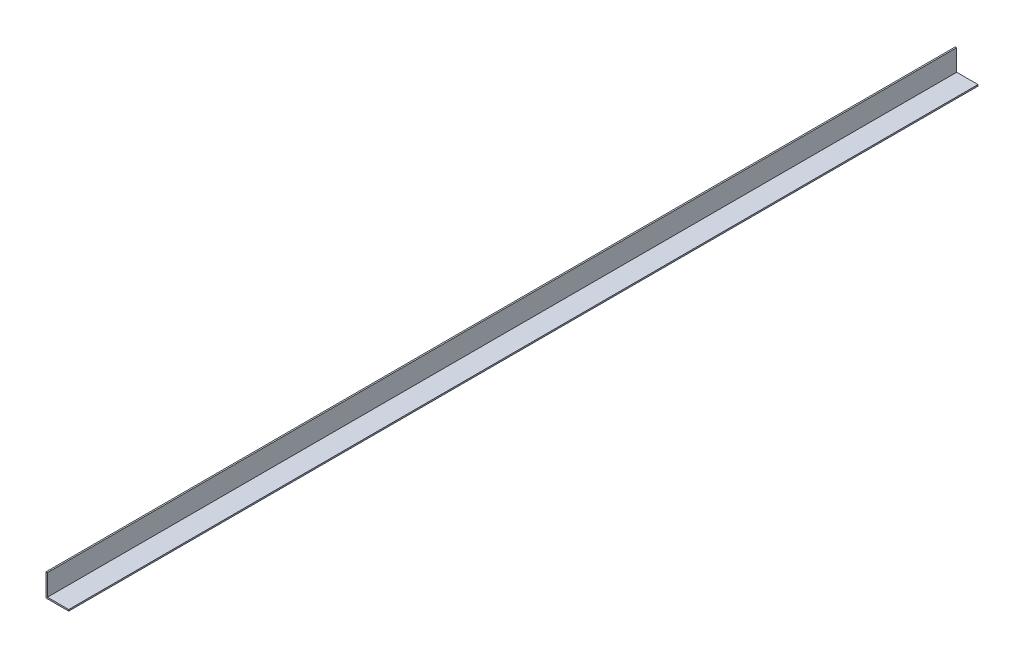
SolidWorks part; units mm, degrees
material "ASTM A36 Acero"
ref_plane "Alzado" through (0, 0, 0) normal (0, 0, 1) x (1, 0, 0)
ref_plane "Planta" through (0, 0, 0) normal (0, 1, 0) x (1, 0, 0)
ref_plane "Vista lateral" through (0, 0, 0) normal (1, 0, 0) x (0, 0, -1)
sketch "Croquis1" plane through (0, 0, 0) normal (0, 0, 1) x (1, 0, 0)
  line L0 (0, 152.4) -> (0, 0)
  line L1 (0, 0) -> (152.4, 0)
  line L2 (152.4, 0) -> (152.4, 9.53)
  line L3 (152.4, 9.53) -> (9.53, 9.53)
  line L4 (9.53, 9.53) -> (9.53, 152.4)
  line L5 (9.53, 152.4) -> (0, 152.4)
  dimension "D1" = 9.53
  dimension "D2" = 152.4
extrude "Saliente-Extruir1" add sketch "Croquis1" against normal blind 6100
